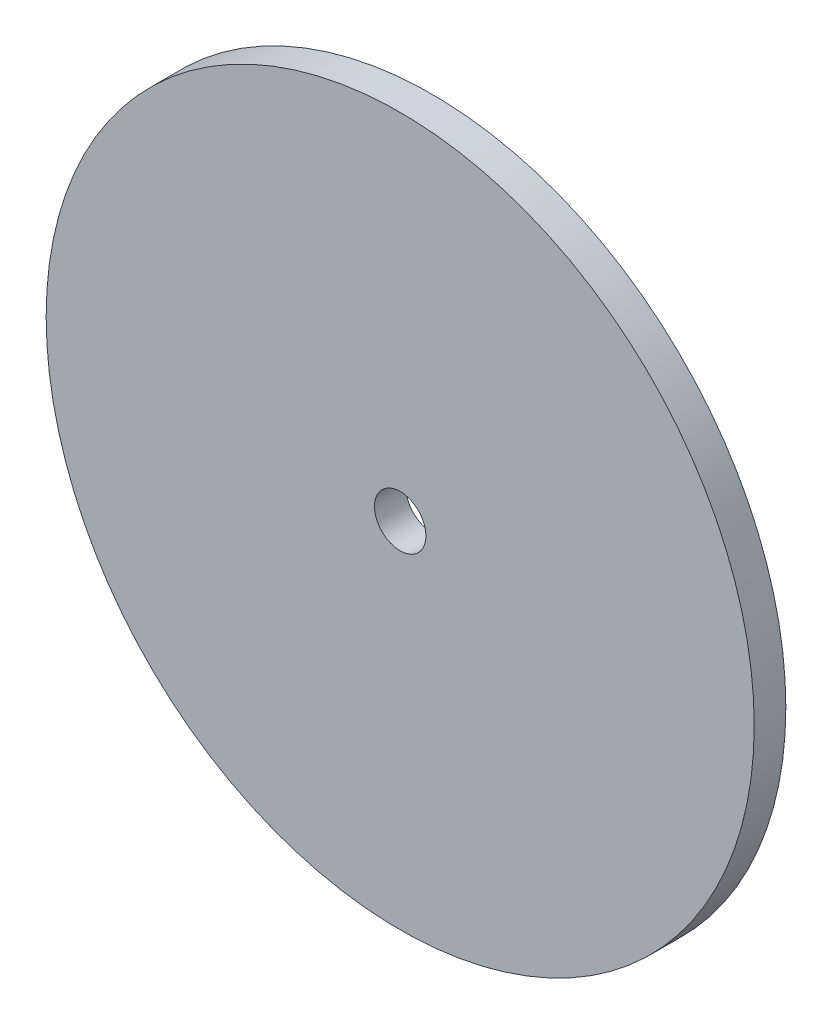
SolidWorks part; units mm, degrees
ref_plane "Front Plane" through (0, 0, 0) normal (0, 0, 1) x (1, 0, 0)
ref_plane "Top Plane" through (0, 0, 0) normal (0, 1, 0) x (1, 0, 0)
ref_plane "Right Plane" through (0, 0, 0) normal (1, 0, 0) x (0, 0, -1)
sketch "Sketch1" plane through (0, 0, 0) normal (0, 0, 1) x (1, 0, 0)
  circle A0 centre (-72.3348, 41.0776) radius 35.56
  circle A1 centre (-72.3348, 41.0776) radius 2.5828
extrude "Boss-Extrude1" add sketch "Sketch1" along normal blind 3.175
